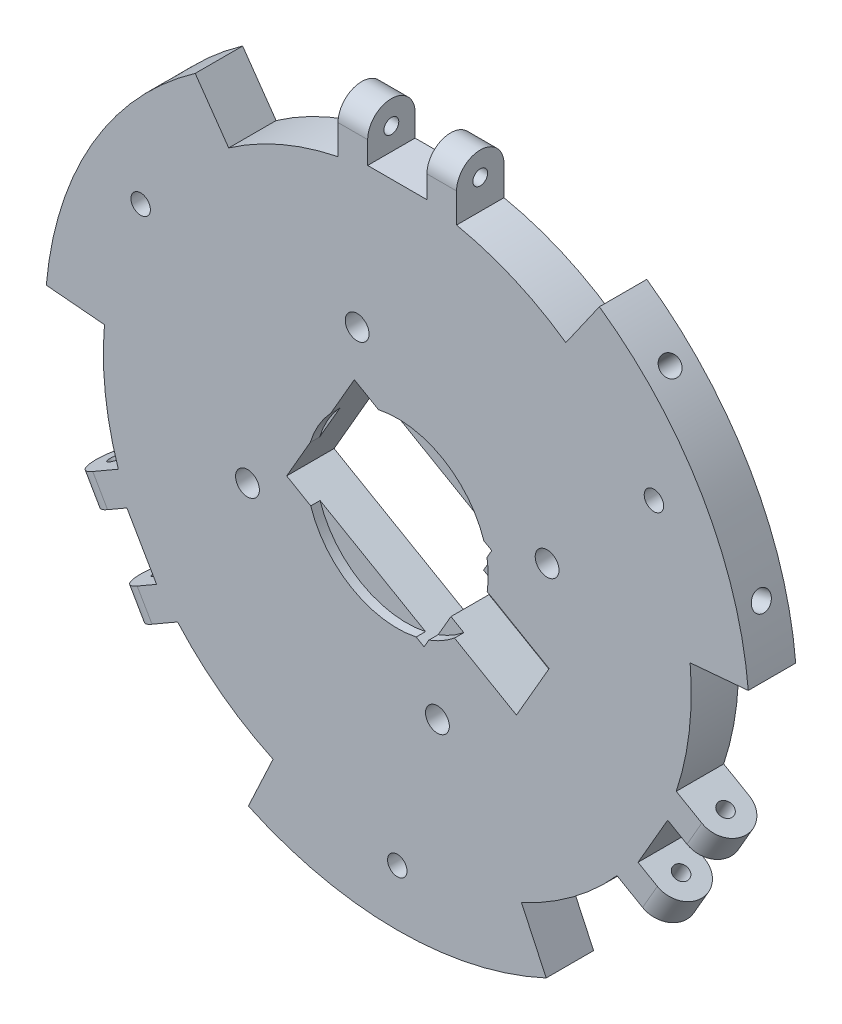
SolidWorks part; units mm, degrees
material "6061 Alloy"
ref_plane "Front Plane" through (0, 0, 0) normal (0, 0, 1) x (1, 0, 0)
ref_plane "Top Plane" through (0, 0, 0) normal (0, 1, 0) x (1, 0, 0)
ref_plane "Right Plane" through (0, 0, 0) normal (1, 0, 0) x (0, 0, -1)
sketch "Sketch1" plane through (0, 0, 0) normal (0, 0, 1) x (1, 0, 0)
  circle A0 centre (0, 0) radius 76.2
  dimension "D1" = 152.4
extrude "Boss-Extrude1" add sketch "Sketch1" along normal blind 2.54
sketch "Sketch2" plane through (0, 0, 0) normal (0, 0, -1) x (-1, 0, 0)
  circle A0 centre (0, 0) radius 76.2
  circle A1 centre (0, 0) radius 57.15
  circle A2 centre (0, 0) radius 76.2 construction
  dimension "D1" = 19.05
extrude "Boss-Extrude2" add sketch "Sketch2" along normal blind 2.54
sketch "Sketch3" plane through (0, 0, -2.54) normal (0, 0, -1) x (-1, 0, 0)
  line L0 (0, 0) -> (0, 76.2) construction
  line L1 (6.35, 63.235) -> (-6.35, 63.235)
  line L2 (-6.35, 63.235) -> (-6.35, 75.935)
  line L3 (6.35, 63.235) -> (6.35, 75.935)
  line L6 (-6.35, 75.935) -> (-6.35, 78.5864)
  line L7 (-6.35, 78.5864) -> (6.35, 78.5864)
  line L8 (6.35, 75.935) -> (6.35, 78.5864)
  circle A0 centre (0, 0) radius 76.2 construction
  point P8 (0, 63.235)
  dimension "D1" = 12.7
  dimension "D2" = 12.7
extrude "Cut-Extrude1" cut sketch "Sketch3" against normal through all both and the other way through all
sketch "Sketch4" plane through (0, 0, -2.54) normal (0, 0, -1) x (-1, 0, 0)
  line L0 (0, 0) -> (-43.7065, 62.4194)
  line L2 (-36.1295, 51.5983) -> (-43.7065, 62.4194)
  line L4 (-12.7, 61.6963) -> (-12.7, 75.1342)
  line L8 (12.7, 61.6963) -> (12.7, 75.1342)
  line L11 (-12.7, 61.6963) -> (-12.7, 75.935)
  line L15 (36.1295, 51.5983) -> (43.7065, 62.4194)
  line L18 (12.7, 61.6963) -> (12.7, 75.935)
  line L20 (0, 0) -> (-76.0928, 0)
  line L21 (83.27, 0) -> (-83.27, 0) construction
  line L22 (0, 0) -> (43.7065, 62.4194)
  circle A3 centre (0, 0) radius 76.2 construction
  arc A8 (-34.2322, 68.0779) -> (-43.7065, 62.4194) centre (0, 0) ccw
  arc A9 (43.7065, 62.4194) -> (12.7, 75.1342) centre (0, 0) ccw
  arc A10 (-12.7, 75.1342) -> (-43.7065, 62.4194) centre (0, 0) ccw
  arc A12 (36.1295, 51.5983) -> (12.7, 61.6963) centre (0, 0) ccw
  arc A13 (-12.7, 61.6963) -> (-36.1295, 51.5983) centre (0, 0) ccw
  point P6 (0, 53.7068)
  point P18 (0, 50.8)
  dimension "D1" = 55
  dimension "D2" = 55
extrude "Cut-Extrude2" cut sketch "Sketch4" against normal through all both and the other way through all
sketch "Sketch5" plane through (0, 0, 0) normal (0, 0, -1) x (-1, 0, 0)
  circle A0 centre (0, 0) radius 6.35
  dimension "D1" = 12.7
extrude "Cut-Extrude3" cut sketch "Sketch5" against normal through all both and the other way through all
sketch "Sketch6" plane through (12.7, 0, 0) normal (1, 0, 0) x (0, 0, -1)
  line L0 (-2.54, 61.6963) -> (-2.54, 75.1342) construction
  line L1 (-2.54, 75.1342) -> (2.54, 75.1342) construction
  circle A0 centre (-2.54, 68.0222) radius 1.5875
  dimension "D1" = 3.175
  dimension "D2" = 7.112
extrude "Cut-Extrude4" cut sketch "Sketch6" against normal blind 25.4
pattern_circular "CirPattern3" count 3 over 360 about axis through (0, 0, 0) along (0, 0, 1) of "Cut-Extrude4", "Cut-Extrude2", "Cut-Extrude1"
sketch "Sketch8" plane through (0, 0, 0) normal (0, 0, -1) x (-1, 0, 0)
  line L6 (0, 0) -> (-75.5481, 9.9461)
  line L15 (-46.3876, 60.4535) -> (0, 0)
  line L16 (75.5481, 9.9461) -> (0, 0)
  line L17 (0, 0) -> (46.3876, 60.4535)
  line L18 (-29.1605, -70.3996) -> (0, 0)
  line L19 (0, 0) -> (29.1605, -70.3996)
  arc A3 (75.5481, 9.9461) -> (46.3876, 60.4535) centre (0, 0) ccw
  arc A5 (-29.1605, -70.3996) -> (29.1605, -70.3996) centre (0, 0) ccw
  arc A6 (75.5481, 9.9461) -> (46.3876, 60.4535) centre (0, 0) ccw
  arc A7 (-46.3876, 60.4535) -> (-75.5481, 9.9461) centre (0, 0) ccw
  arc A8 (-29.1605, -70.3996) -> (29.1605, -70.3996) centre (0, 0) ccw
  point P9 (0, 0)
  dimension "D1" = 45
  dimension "D2" = 3
sketch "Sketch11" plane through (0, 0, 0) normal (0, 0, -1) x (-1, 0, 0)
  line L0 (0, 0) -> (0, -76.2) construction
  line L1 (0, -76.2) -> (9.0736, -76.2) construction
  line L2 (0, -76.2) -> (-9.57, -76.2) construction
  circle A0 centre (0, 0) radius 76.2 construction
sketch "Sketch12" plane through (0, 0, 0) normal (0, 0, -1) x (-1, 0, 0)
  line L7 (-3.8923, 11.8217) -> (-26.3471, 50.7144)
  line L14 (3.8923, 11.8217) -> (26.3471, 50.7144)
  line L16 (0, 12.446) -> (0, 57.15) construction
  arc A3 (26.3471, 50.7144) -> (-26.3471, 50.7144) centre (0, 0) ccw
  arc A4 (3.8923, 11.8217) -> (-3.8923, 11.8217) centre (0, 0) ccw
  point P19 (-6.223, 10.7786)
sketch "Sketch14" plane through (12.7, 0, 0) normal (1, 0, 0) x (0, 0, -1)
  line L3 (-7.62, 68.0222) -> (-7.62, 77.2519)
  line L4 (-7.62, 77.2519) -> (2.54, 77.2519)
  line L5 (2.54, 68.0222) -> (2.54, 77.2519)
  arc A0 (2.54, 68.0222) -> (-7.62, 68.0222) centre (-2.54, 68.0222) ccw
extrude "Cut-Extrude17" cut sketch "Sketch14" against normal blind 25.4
pattern_circular "CirPattern9" count 3 over 360 about axis through (0, 0, 0) along (0, 0, 1) of "Cut-Extrude17"
sketch "Sketch15" plane through (0, 0, 0) normal (0, 0, -1) x (-1, 0, 0)
  circle A0 centre (0, 0) radius 57.15 construction
  circle A1 centre (0, 0) radius 57.15
extrude "Boss-Extrude6" add sketch "Sketch15" along normal blind 2.54
sketch "Sketch19" plane through (0, 0, 2.54) normal (0, 0, 1) x (1, 0, 0)
  line L0 (0, 0) -> (0, -76.2)
  line L1 (0, -76.2) -> (0, 0)
  line L2 (0, 0) -> (19.722, -73.6035)
  line L3 (19.722, -73.6035) -> (0, 0)
  line L4 (0, 0) -> (-19.722, -73.6035)
  arc A0 (-29.1605, -70.3996) -> (29.1605, -70.3996) centre (0, 0) ccw construction
  dimension "D1" = 15
  dimension "D2" = 15
ref_plane "Plane1" through (19.722, -73.6035, 2.54) normal (0.2588, -0.9659, 0) x (-0.9659, -0.2588, 0)
ref_plane "Plane2" through (-19.722, -73.6035, 2.54) normal (-0.2588, -0.9659, 0) x (-0.9659, 0.2588, 0)
sketch "Sketch20" plane through (19.722, -73.6035, 2.54) normal (0.2588, -0.9659, 0) x (-0.9659, -0.2588, 0)
  line L0 (0, 0.0141) -> (0, 5.1079) construction
  circle A1 centre (0, 0.0141) radius 2.0828
  dimension "D1" = 4.1656
sketch "Sketch21" plane through (-19.722, -73.6035, 2.54) normal (-0.2588, -0.9659, 0) x (-0.9659, 0.2588, 0)
  line L0 (-38.1, 0) -> (0, 0) construction
  line L1 (0, 0) -> (-38.1, 0) construction
  circle A0 centre (0, 0) radius 2.0828
  dimension "D1" = 4.1656
extrude "Cut-Extrude20" cut sketch "Sketch20" against normal blind 12.7 contours A1
extrude "Cut-Extrude21" cut sketch "Sketch21" against normal blind 12.7 contours A0
pattern_circular "CirPattern10" count 3 over 360 about axis through (0, 0, 0) along (0, 0, 1) of "Cut-Extrude21", "Cut-Extrude20"
mirror "Mirror1" about plane through (0, 0, 2.54) normal (0, 0, 1) of "Boss-Extrude1", "Cut-Extrude2", "Boss-Extrude2", "Cut-Extrude1", "Cut-Extrude3", "Cut-Extrude4", "CirPattern3", "Cut-Extrude17", "CirPattern9", "Boss-Extrude6", "Cut-Extrude20", "Cut-Extrude21", "CirPattern10"
sketch "Sketch22" plane through (0, 0, 7.62) normal (0, 0, 1) x (1, 0, 0)
  circle A0 centre (0, 0) radius 6.35 construction
  circle A1 centre (0, 0) radius 6.35
extrude "Cut-Extrude22" cut sketch "Sketch22" against normal blind 12.7
sketch "Sketch23" plane through (0, 0, -2.54) normal (0, 0, -1) x (-1, 0, 0)
  line L0 (0, 0) -> (0, -76.2) construction
  circle A0 centre (0, -63.5) radius 2.0828
  circle A1 centre (-54.9926, 31.75) radius 2.0828
  circle A2 centre (54.9926, 31.75) radius 2.0828
  point P11 (0, 0)
  dimension "D1" = 4.1656
  dimension "D2" = 63.5
  dimension "D3" = 3
extrude "Cut-Extrude23" cut sketch "Sketch23" against normal up to surface (10.16 mm away)
sketch "Sketch25" plane through (0, 0, 7.62) normal (0, 0, 1) x (1, 0, 0)
  circle A0 centre (0, 0) radius 75.5
  circle A1 centre (0, 0) radius 95.5659
  dimension "D1" = 151
extrude "Cut-Extrude27" cut sketch "Sketch25" against normal through all both and the other way through all
sketch "Sketch26" plane through (0, 0, 7.62) normal (0, 0, 1) x (1, 0, 0)
  line L0 (8.6016, -32.1016) -> (-32.1016, -8.6016)
  line L1 (8.6016, -32.1016) -> (32.1016, 8.6016)
  line L2 (-32.1016, -8.6016) -> (-8.6016, 32.1016)
  line L3 (32.1016, 8.6016) -> (-8.6016, 32.1016)
  line L4 (8.6016, -32.1016) -> (-8.6016, 32.1016) construction
  line L5 (-32.1016, -8.6016) -> (32.1016, 8.6016) construction
  line L6 (-36.1295, 51.5983) -> (-62.7501, 5.4899)
  circle A5 centre (-8.6016, 32.1016) radius 2.55
  circle A6 centre (32.1016, 8.6016) radius 2.55
  circle A7 centre (8.6016, -32.1016) radius 2.55
  circle A8 centre (-32.1016, -8.6016) radius 2.55
  point P1 (0, 0)
  point P11 (-64.4991, 39.2443)
  dimension "D1" = 5.1
  dimension "D2" = 47
  dimension "D3" = 47
extrude "Cut-Extrude28" cut sketch "Sketch26" against normal up to surface (10.16 mm away) contours A5 | A6 | A8 | A7 up to face at (-2.0828, -63.5, -2.54)
sketch "Sketch27" plane through (0, 0, -2.54) normal (0, 0, -1) x (-1, 0, 0)
  line L0 (65.3849, 37.75) -> (0, 0) construction
  line L1 (0, 0) -> (29.6255, -51.3129) construction
  circle A0 centre (0, 0) radius 6.35
  circle A1 centre (8.1, -14.0296) radius 1.45
  circle A2 centre (11.5, -19.9186) radius 1.5
  arc A3 (75.2127, 6.5803) -> (43.305, 61.846) centre (0, 0) ccw construction
  circle A4 centre (-8.1, 14.0296) radius 1.45
  circle A5 centre (-11.5, 19.9186) radius 1.5
  dimension "D1" = 3
  dimension "D2" = 2.9
  dimension "D3" = 32.4
  dimension "D4" = 46
sketch "Sketch28" plane through (0, 0, 7.62) normal (0, 0, 1) x (1, 0, 0)
  line L0 (-65.3849, 37.75) -> (0, 0) construction
  line L1 (0, 0) -> (-31.4949, -54.5508) construction
  line L2 (-9.2045, 22.0574) -> (-23.7045, -3.0574)
  line L3 (-23.7045, -3.0574) -> (5.7404, -20.0574)
  line L4 (5.7404, -20.0574) -> (20.2404, 5.0574)
  line L5 (20.2404, 5.0574) -> (-9.2045, 22.0574)
  arc A0 (-43.305, 61.846) -> (-75.2127, 6.5803) centre (0, 0) ccw construction
  arc A1 (-47.0805, -41.8467) -> (-26.6207, -57.0882) centre (0, 0) ccw construction
  point P6 (0, 0)
  point P13 (-16.4545, 9.5)
  dimension "D1" = 29
  dimension "D2" = 34
  dimension "D3" = 15
extrude "Cut-Extrude29" cut sketch "Sketch28" against normal through all contours L5 L2 L3 L4
sketch "Sketch29" plane through (0, 0, 7.62) normal (0, 0, 1) x (1, 0, 0)
  circle A0 centre (0, 0) radius 19.5
  dimension "D1" = 39
extrude "Cut-Extrude30" cut sketch "Sketch29" against normal blind 2
sketch "Sketch30" plane through (0, 0, 7.62) normal (0, 0, 1) x (1, 0, 0)
  line L0 (54.7631, -31.6175) -> (0, 0)
  line L1 (51.5881, -37.1167) -> (57.9381, -26.1182) construction
  line L2 (25.5361, -22.8262) -> (32.5361, -10.7018)
  line L3 (32.5361, -10.7018) -> (3.5, 6.0622)
  line L4 (3.5, 6.0622) -> (-3.5, -6.0622)
  line L5 (-3.5, -6.0622) -> (25.5361, -22.8262)
  point P8 (29.0361, -16.764)
  dimension "D1" = 14
  dimension "D2" = 33.528
extrude "Cut-Extrude31" cut sketch "Sketch30" against normal through all contours L3 L4 L0 L2 | L4 L5 L2 L0
